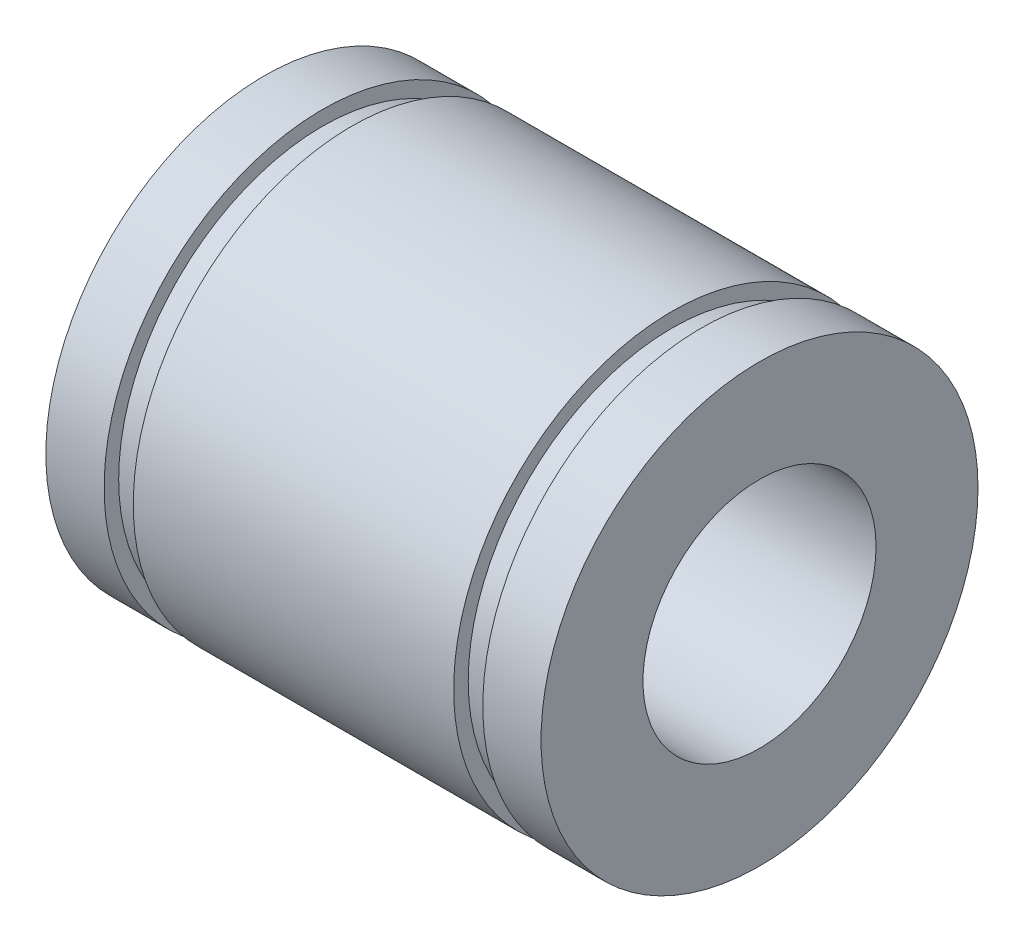
SolidWorks part; units mm, degrees
ref_plane "Front Plane" through (0, 0, 0) normal (0, 0, 1) x (1, 0, 0)
ref_plane "Top Plane" through (0, 0, 0) normal (0, 1, 0) x (1, 0, 0)
ref_plane "Right Plane" through (0, 0, 0) normal (1, 0, 0) x (0, 0, -1)
sketch "Sketch1" plane through (0, 0, 0) normal (1, 0, 0) x (0, 0, -1)
  circle A0 centre (0, 0) radius 4
  circle A1 centre (0, 0) radius 7.5
  dimension "D1" = 8
  dimension "D2" = 15
extrude "Boss-Extrude1" add sketch "Sketch1" along normal blind 2
sketch "Sketch2" plane through (2, 0, 0) normal (1, 0, 0) x (0, 0, -1)
  circle A0 centre (0, 0) radius 4
  circle A1 centre (0, 0) radius 7
  dimension "D1" = 14
extrude "Boss-Extrude2" add sketch "Sketch2" along normal blind 1
sketch "Sketch3" plane through (3, 0, 0) normal (1, 0, 0) x (0, 0, -1)
  circle A0 centre (0, 0) radius 4
  circle A1 centre (0, 0) radius 7.5
  dimension "D1" = 15
extrude "Boss-Extrude3" add sketch "Sketch3" along normal blind 11
sketch "Sketch4" plane through (14, 0, 0) normal (1, 0, 0) x (0, 0, -1)
  circle A0 centre (0, 0) radius 4
  circle A1 centre (0, 0) radius 7
  dimension "D1" = 14
extrude "Boss-Extrude4" add sketch "Sketch4" along normal blind 1
sketch "Sketch5" plane through (15, 0, 0) normal (1, 0, 0) x (0, 0, -1)
  circle A0 centre (0, 0) radius 4
  circle A1 centre (0, 0) radius 7.5
  dimension "D1" = 15
extrude "Boss-Extrude5" add sketch "Sketch5" along normal blind 2
